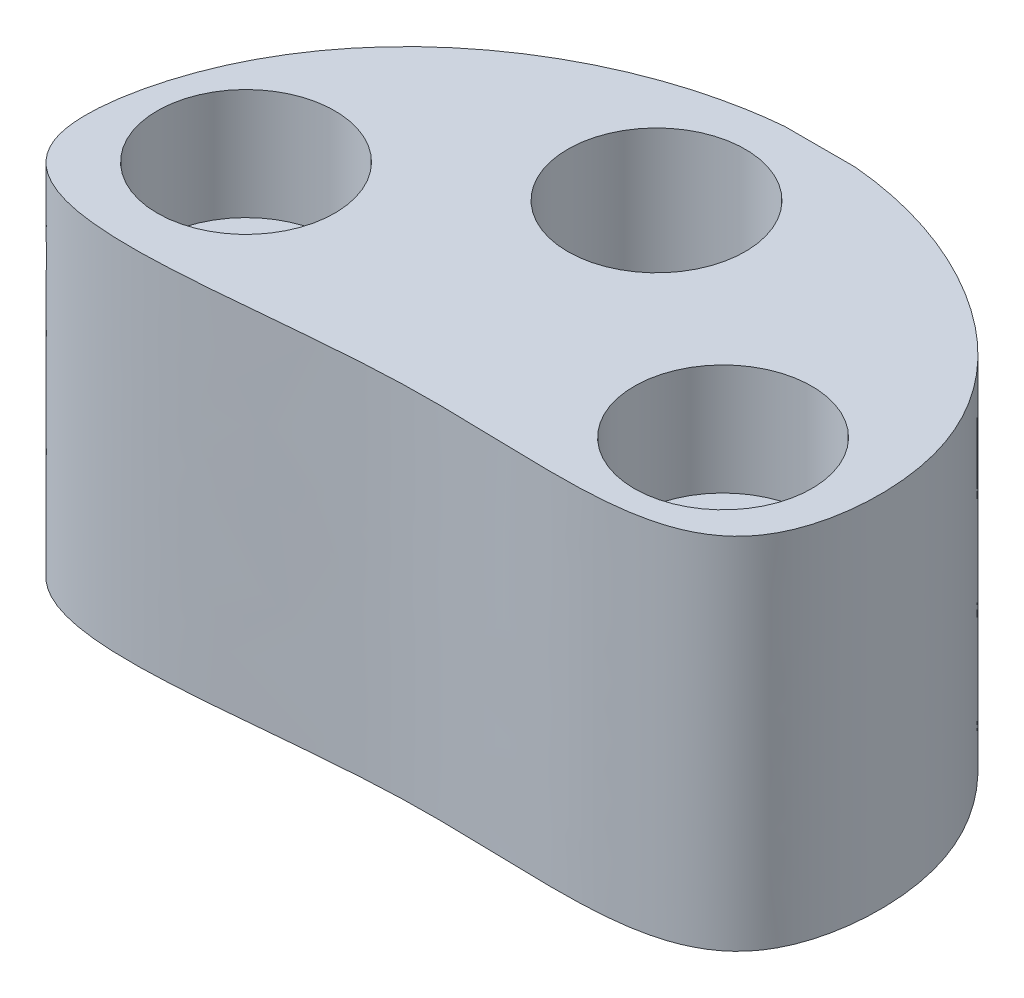
SolidWorks part; units mm, degrees
ref_plane "Front Plane" through (0, 0, 0) normal (0, 0, 1) x (1, 0, 0)
ref_plane "Top Plane" through (0, 0, 0) normal (0, 1, 0) x (1, 0, 0)
ref_plane "Right Plane" through (0, 0, 0) normal (1, 0, 0) x (0, 0, -1)
sketch "Sketch2" plane through (0, 0, 0) normal (0, 1, 0) x (1, 0, 0)
  circle A0 centre (0, 0) radius 50
extrude "Boss-Extrude1" add sketch "Sketch2" along normal blind 16.2 contours A0
sketch "Sketch4" plane through (0, 16.2, 0) normal (0, 1, 0) x (1, 0, 0)
  circle A0 centre (0, 0) radius 4
  dimension "D1" = 8
sketch "Sketch7" plane through (0, 16.2, 0) normal (0, 1, 0) x (1, 0, 0)
  circle A0 centre (-10.75, -7.75) radius 4
  dimension "D1" = 8
extrude "Cut-Extrude2" cut sketch "Sketch7" against normal blind 5 contours A0
mirror "Mirror1" about plane through (0, 0, 0) normal (1, 0, 0) of "Cut-Extrude2"
sketch "Sketch10" plane through (0, 16.2, 0) normal (0, 1, 0) x (1, 0, 0)
  line L0 (-53.2107, 12.4951) -> (32.4432, -51.9554)
  line L1 (-53.2107, 12.4951) -> (-75.9409, -17.713)
  line L2 (32.4432, -51.9554) -> (9.713, -82.1635)
  line L3 (-75.9409, -17.713) -> (9.713, -82.1635)
  line L4 (47.0489, 22.6826) -> (-26.1438, -56.7455)
  line L5 (47.0489, 22.6826) -> (79.9451, -7.6312)
  line L6 (-26.1438, -56.7455) -> (6.7524, -87.0592)
  line L7 (79.9451, -7.6312) -> (6.7524, -87.0592)
  line L8 (-36.4602, 41.6265) -> (-30.04, -35.8841)
  line L9 (-36.4602, 41.6265) -> (-89.1249, 37.2643)
  line L10 (-30.04, -35.8841) -> (-82.7047, -40.2463)
  line L11 (-89.1249, 37.2643) -> (-82.7047, -40.2463)
  line L12 (0, 56.1022) -> (-64.5758, -2.6089)
  line L13 (0, 56.1022) -> (-28.0305, 86.9326)
  line L14 (-64.5758, -2.6089) -> (-92.6063, 28.2215)
  line L15 (-28.0305, 86.9326) -> (-92.6063, 28.2215)
  line L16 (14.9283, 52.2816) -> (55.6195, 7.5257)
  line L17 (14.9283, 52.2816) -> (36.6671, 72.0461)
  line L18 (55.6195, 7.5257) -> (77.3583, 27.2902)
  line L19 (36.6671, 72.0461) -> (77.3583, 27.2902)
  circle M16 centre (0, 0) radius 50
extrude "Cut-Extrude6" cut sketch "Sketch10" against normal blind 17 contours L12 L8 M16 | L12 L8 M16 | L8 L12 L0 M16 | L10 L8 L0 M16 | L8 L10 L4 L0 M16 | L0 L4 M16 | L16 L4 L0 M16 | L16 L4 M16
sketch "Sketch11" plane through (0, 16.2, 0) normal (0, 1, 0) x (1, 0, 0)
  line L0 (40.8019, 27.4875) -> (42.9007, 10.0278)
  line L1 (40.8019, 27.4875) -> (50.4505, 28.6473)
  line L2 (42.9007, 10.0278) -> (52.5493, 11.1876)
  line L3 (50.4505, 28.6473) -> (52.5493, 11.1876)
sketch "Sketch13" plane through (0, 16.2, 0) normal (0, 1, 0) x (1, 0, 0)
  line L0 (-27.6296, -15.0928) -> (26.5505, 44.8666)
  line L1 (-27.6296, -15.0928) -> (-55.6994, 10.2715)
  line L2 (26.5505, 44.8666) -> (-1.5193, 70.2308)
  line L3 (-55.6994, 10.2715) -> (-1.5193, 70.2308)
  line L4 (26.5505, -9.5921) -> (-32.6864, 45.8779)
  line L5 (26.5505, -9.5921) -> (65.0475, 31.5192)
  line L6 (-32.6864, 45.8779) -> (5.8106, 86.9892)
  line L7 (65.0475, 31.5192) -> (5.8106, 86.9892)
  line M1 (44.4265, 19.8368) -> (21.3593, 45.2082)
  arc M2 (21.3593, 45.2082) -> (-7.3012, 49.4641) centre (0, 0) ccw
  line M3 (-7.3012, 49.4641) -> (-35.0219, 24.261)
  line M4 (-35.0219, 24.261) -> (-32.7735, -2.8829)
  line M5 (-32.7735, -2.8829) -> (0.4522, -27.8837)
  line M6 (0.4522, -27.8837) -> (44.4265, 19.8368)
extrude "Cut-Extrude8" cut sketch "Sketch13" against normal blind 17 contours L0 L4 M3 M4 M5 | L4 L0 M1 M2 M3 | L4 L0 M6 M1
extrude "Cut-Extrude9" cut sketch "Sketch11" against normal blind 17
extrude "Cut-Extrude10" cut sketch "Sketch4" against normal blind 17
sketch "Sketch14" plane through (0, 16.2, 0) normal (0, 1, 0) x (1, 0, 0)
  line L0 (-15.982, 5.7775) -> (20.2041, 5.7775)
  line L1 (-15.982, 5.7775) -> (-15.982, 17.0907)
  line L2 (20.2041, 5.7775) -> (20.2041, 17.0907)
  line L3 (-15.982, 17.0907) -> (20.2041, 17.0907)
  line L4 (-18.7903, 0.8832) -> (-18.7903, -22.1444)
  line L5 (-18.7903, 0.8832) -> (-26.2522, 0.8832)
  line L6 (-18.7903, -22.1444) -> (-26.2522, -22.1444)
  line L7 (-26.2522, 0.8832) -> (-26.2522, -22.1444)
  line L8 (-18.1773, -13.8658) -> (15.9517, -13.8658)
  line L9 (-18.1773, -13.8658) -> (-18.1773, -29.2051)
  line L10 (15.9517, -13.8658) -> (15.9517, -29.2051)
  line L11 (-18.1773, -29.2051) -> (15.9517, -29.2051)
  line L12 (-23.144, -10.1287) -> (0.4522, -27.8837) construction
  line L13 (17.9575, 2.1669) -> (17.9575, -14.4418)
  line L14 (17.9575, 2.1669) -> (25.7404, 2.1669)
  line L15 (17.9575, -14.4418) -> (25.7404, -14.4418)
  line L16 (25.7404, 2.1669) -> (25.7404, -14.4418)
extrude "Cut-Extrude11" cut sketch "Sketch14" against normal blind 17
sketch "Sketch15" plane through (0, 16.2, 0) normal (0, 1, 0) x (1, 0, 0)
  line L0 (-8.7709, 5.7775) -> (10.1372, 5.7775) construction
  line L1 (-11.7174, 4.5453) -> (-7.2216, -0.5736)
  line L2 (-11.7174, 4.5453) -> (-15.2294, 1.4607)
  line L3 (-7.2216, -0.5736) -> (-10.7336, -3.6581)
  line L4 (-15.2294, 1.4607) -> (-10.7336, -3.6581)
  spline S0 degree 3 poles (-15.0455, -0.2883) (-3.1276, 7.4971) (10.3102, 4.6691) (17.0649, -2.2158) (16.1424, -14.5523) (0.751, -11.1767) (-17.3252, -16.122) (-15.0455, -0.2883) (-3.1276, 7.4971) (10.3102, 4.6691) knots -0.506939 -0.292607 -0.235973 0 0.124519 0.240488 0.321006 0.493061 0.707393 0.764027 1 1.124519 1.240488 1.321006 only from (0, 5.7775) to (0, 5.7775)
  line M1 (-18.7903, -5.3106) -> (-18.7903, -13.4046)
  line M2 (-18.7903, -13.4046) -> (-18.1773, -13.8658)
  line M3 (-18.1773, -13.8658) -> (13.3697, -13.8658)
  line M4 (13.3697, -13.8658) -> (17.9575, -8.8871)
  line M5 (17.9575, -8.8871) -> (17.9575, -1.5455)
  line M6 (17.9575, -1.5455) -> (10.1372, 5.7775)
  line M7 (10.1372, 5.7775) -> (-8.7709, 5.7775)
  line M8 (-8.7709, 5.7775) -> (-18.7903, -5.3106)
extrude "Cut-Extrude13" cut sketch "Sketch15" against normal blind 17 contours L1 S0 M7 M8 | L4 S0 L1 M8 | S0 L4 M7 M8 M1 M2 M3 M4 M5 M6
